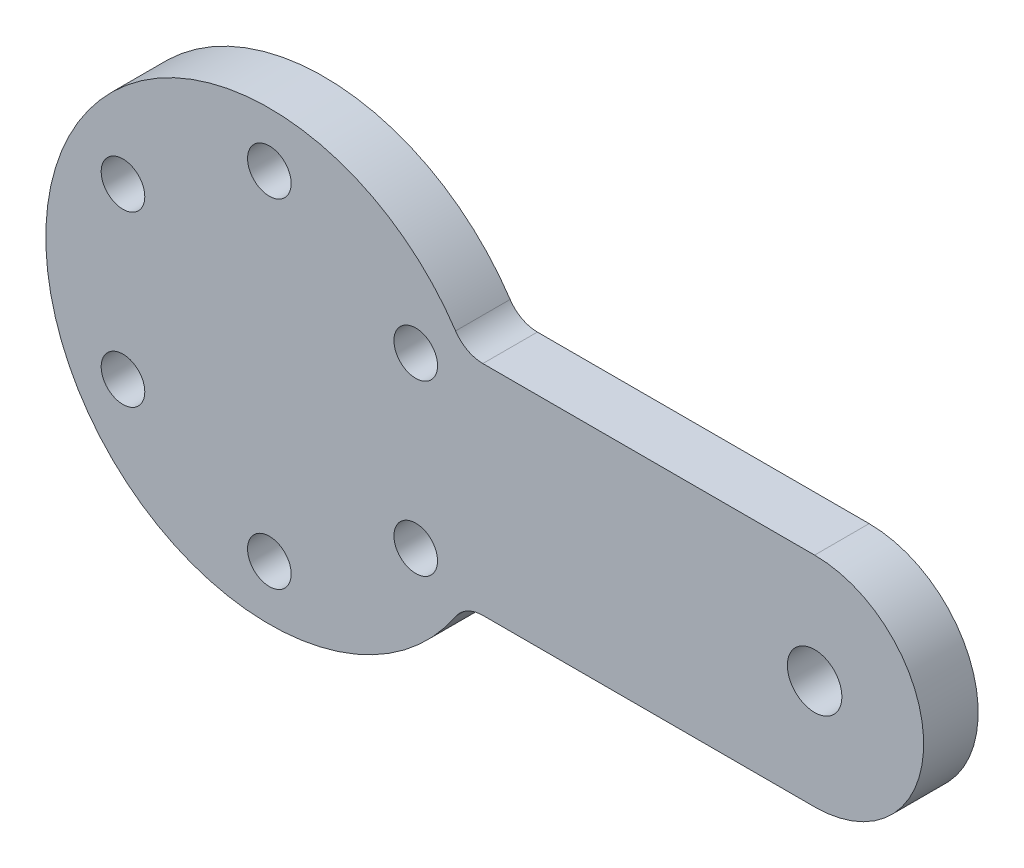
SolidWorks part; units mm, degrees
ref_plane "前基準面" through (0, 0, 0) normal (0, 0, 1) x (1, 0, 0)
ref_plane "上基準面" through (0, 0, 0) normal (0, 1, 0) x (1, 0, 0)
ref_plane "右基準面" through (0, 0, 0) normal (1, 0, 0) x (0, 0, -1)
sketch "草圖1" plane through (0, 0, 0) normal (0, 0, 1) x (1, 0, 0)
  line L0 (-80, 0) -> (-72.5, 0) construction
  line L1 (17.8955, 10) -> (50, 10)
  line L2 (17.8955, -10) -> (50, -10)
  line L3 (0, 0) -> (50, 0) construction
  arc A1 (50, -10) -> (50, 10) centre (50, 0) ccw
  circle A3 centre (50, 0) radius 2.5
  arc A6 (17.8955, 10) -> (17.8955, -10) centre (0, 0) ccw
  point P3 (0, 0)
  dimension "D1" = 10
  dimension "D3" = 5
  dimension "D4" = 41
  dimension "D2" = 50
extrude "填料-伸長1" add sketch "草圖1" along normal mid plane 5
sketch "草圖2" plane through (0, 0, 2.5) normal (0, 0, 1) x (1, 0, 0)
  circle A0 centre (0, 15.5) radius 2
  dimension "D1" = 4
  dimension "D2" = 15.5
extrude "除料-伸長1" cut sketch "草圖2" against normal up to next
pattern_circular "環狀複製排列1" count 6 over 360 about axis through (0, 0, 0) along (0, 0, 1) of "除料-伸長1"
fillet "圓角1" radius 3 2 edges at (17.8955, 10, 0) (17.8955, -10, 0)
